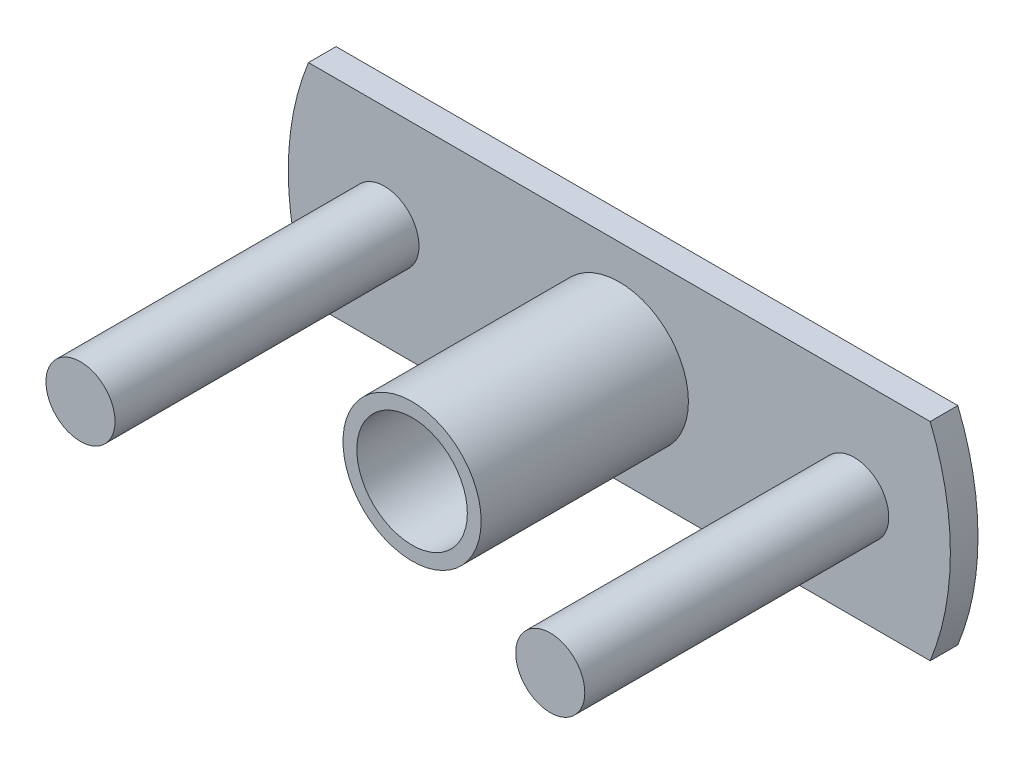
SolidWorks part; units mm, degrees
ref_plane "Front Plane" through (0, 0, 0) normal (0, 0, 1) x (1, 0, 0)
ref_plane "Top Plane" through (0, 0, 0) normal (0, 1, 0) x (1, 0, 0)
ref_plane "Right Plane" through (0, 0, 0) normal (1, 0, 0) x (0, 0, -1)
sketch "Sketch1" plane through (0, 0, 0) normal (0, 0, 1) x (1, 0, 0)
  line L1 (-22.5, -7.5) -> (22.5, -7.5)
  line L3 (-22.5, 7.5) -> (22.5, 7.5)
  line L5 (-22.5, -7.5) -> (22.5, 7.5) construction
  line L6 (-22.5, 7.5) -> (22.5, -7.5) construction
  arc A0 (-22.5, 7.5) -> (-22.5, -7.5) centre (-3.9595, 0) ccw
  arc A3 (22.5, 7.5) -> (22.5, -7.5) centre (3.9595, 0) cw
  point P0 (0, 0)
  dimension "D1" = 45
  dimension "D2" = 15
  dimension "D3" = 20
  dimension "D4" = 20
  dimension "D5" = 36.87
  dimension "D6" = 7.5
extrude "Boss-Extrude1" add sketch "Sketch1" along normal blind 2 contours L3 A3 L1 A0
sketch "Sketch2" plane through (0, 0, 2) normal (0, 0, 1) x (1, 0, 0)
  circle A0 centre (0, 0) radius 5
  dimension "D1" = 10
extrude "Boss-Extrude2" add sketch "Sketch2" along normal blind 15
sketch "Sketch4" plane through (0, 0, 17) normal (0, 0, 1) x (1, 0, 0)
  circle A0 centre (0, 0) radius 4
  dimension "D1" = 8
extrude "Cut-Extrude1" cut sketch "Sketch4" against normal blind 10
sketch "Sketch5" plane through (0, 0, 2) normal (0, 0, 1) x (1, 0, 0)
  circle A0 centre (-17, 0) radius 2.5
  circle A1 centre (17, 0) radius 2.5
  point P4 (0, 0)
  point P7 (0, 0)
  dimension "D1" = 5
  dimension "D2" = 5
  dimension "D3" = 17
  dimension "D4" = 17
extrude "Boss-Extrude3" add sketch "Sketch5" along normal blind 22
